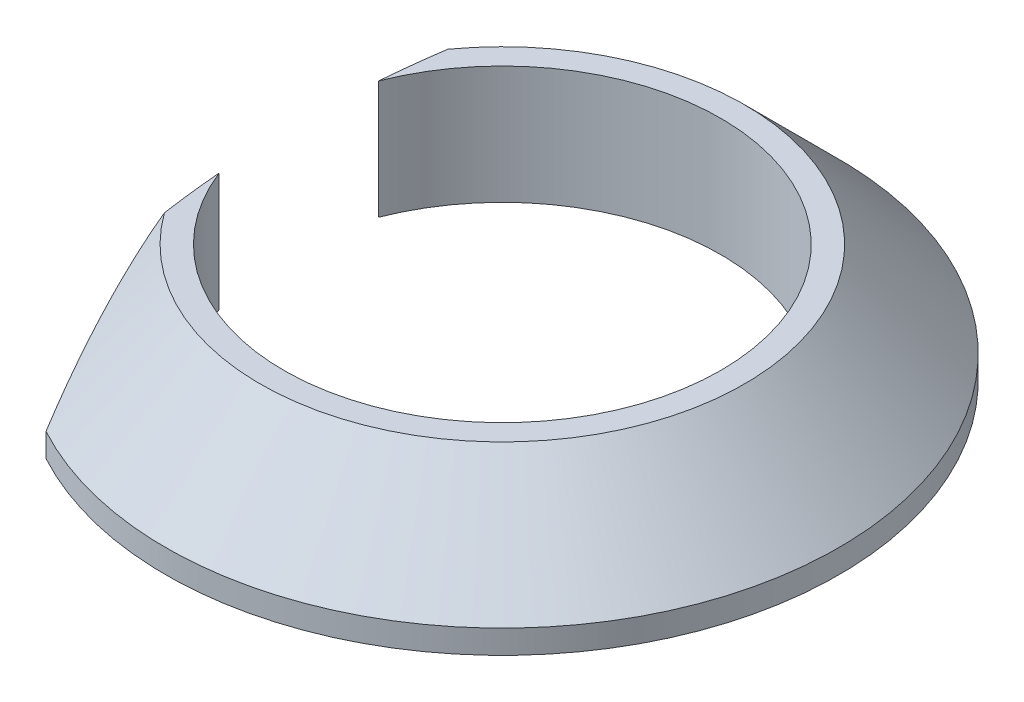
SolidWorks part; units mm, degrees
ref_plane "Front Plane" through (0, 0, 0) normal (0, 0, 1) x (1, 0, 0)
ref_plane "Top Plane" through (0, 0, 0) normal (0, 1, 0) x (1, 0, 0)
ref_plane "Right Plane" through (0, 0, 0) normal (1, 0, 0) x (0, 0, -1)
sketch "Sketch1" plane through (0, 0, 0) normal (0, 1, 0) x (1, 0, 0)
  circle A0 centre (0, 0) radius 104.775 construction
  circle A1 centre (-82.55, 0) radius 22.225 construction
  circle A2 centre (-82.55, 0) radius 23.495
  circle A3 centre (-82.55, 0) radius 26.035
  dimension "D1" = 209.55
  dimension "D2" = 44.45
  dimension "D3" = 46.99
  dimension "D4" = 2.54
extrude "Boss-Extrude1" add sketch "Sketch1" along normal blind 12.7
ref_plane "Plane1" through (0, 0, 26.035) normal (0, 0, 1) x (1, 0, 0)
ref_axis "Axis1" through (-82.55, 12.7, 0) along (0, -1, 0)
ref_plane "Plane2" through (-82.55, 0, 0) normal (-1, 0, 0) x (0, -1, 0)
sketch "Sketch2" plane through (-82.55, 0, 0) normal (-1, 0, 0) x (0, -1, 0)
  line L0 (0, -26.035) -> (0, -36.195)
  line L1 (-2.54, -36.195) -> (-12.7, -26.035)
  line L2 (-12.7, -26.035) -> (0, -26.035) construction
  line L3 (-12.7, 26.035) -> (-12.7, -26.035) construction
  line L4 (-12.7, -26.035) -> (0, -26.035)
  line L5 (-2.54, -36.195) -> (0, -36.195)
  dimension "D1" = 45
  dimension "D2" = 2.54
revolve "Revolve1" add sketch "Sketch2" angle 360 about axis through (-82.55, 12.7, 0) along (0, -1, 0)
sketch "Sketch3" plane through (0, 12.7, 0) normal (0, 1, 0) x (1, 0, 0)
  circle A0 centre (0, 0) radius 104.775 construction
  arc A1 (-99.8318, 31.8028) -> (-99.8318, -31.8028) centre (0, 0) ccw
  circle A2 centre (-82.55, 0) radius 36.195 construction
  arc A3 (-99.8318, 31.8028) -> (-99.8318, -31.8028) centre (-82.55, 0) ccw
extrude "Cut-Extrude1" cut sketch "Sketch3" against normal through all both and the other way through all
